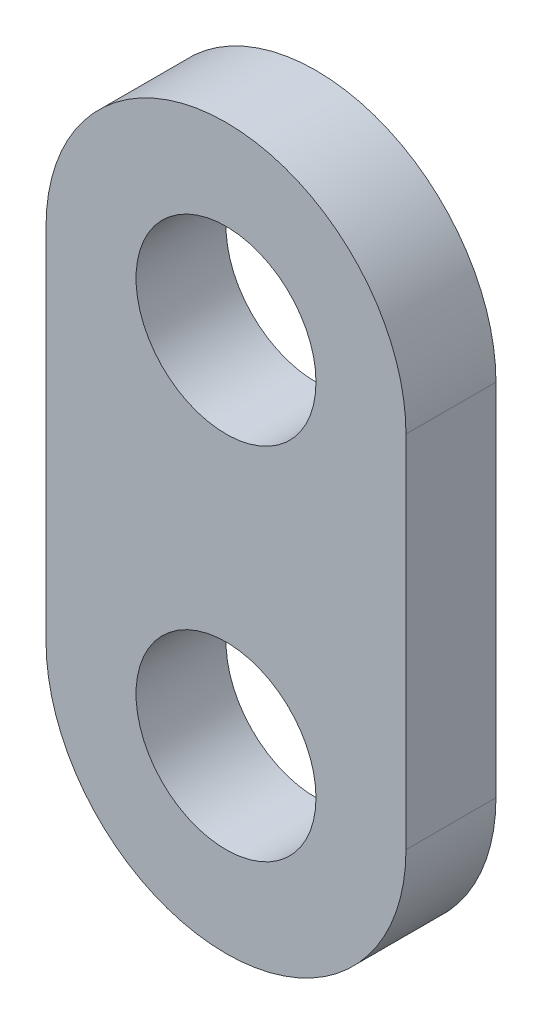
SolidWorks part; units mm, degrees
ref_plane "Front Plane" through (0, 0, 0) normal (0, 0, 1) x (1, 0, 0)
ref_plane "Top Plane" through (0, 0, 0) normal (0, 1, 0) x (1, 0, 0)
ref_plane "Right Plane" through (0, 0, 0) normal (1, 0, 0) x (0, 0, -1)
other "Center of Mass"
sketch "Sketch1" plane through (0, 0, 0) normal (0, 0, 1) x (1, 0, 0)
  line L2 (-50, 50) -> (-50, -50)
  line L4 (50, 50) -> (50, -50)
  arc A0 (50, 50) -> (-50, 50) centre (0, 50) ccw
  arc A1 (-50, -50) -> (50, -50) centre (0, -50) ccw
  circle A2 centre (0, 50) radius 25
  circle A4 centre (0, -50) radius 25
  point P0 (0, 0)
  dimension "D3" = 100
  dimension "D4" = 50
  dimension "D1" = 100
  dimension "D2" = 100
  dimension "D6" = 50
extrude "Boss-Extrude1" add sketch "Sketch1" along normal blind 25
